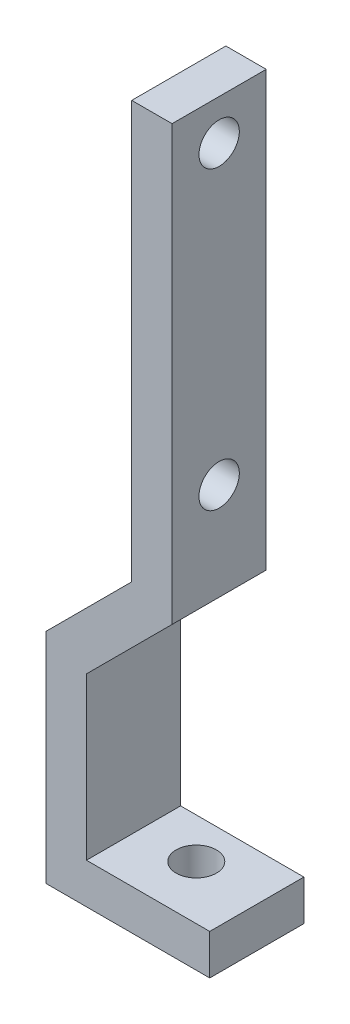
SolidWorks part; units mm, degrees
ref_plane "前视基准面" through (0, 0, 0) normal (0, 0, 1) x (1, 0, 0)
ref_plane "上视基准面" through (0, 0, 0) normal (0, 1, 0) x (1, 0, 0)
ref_plane "右视基准面" through (0, 0, 0) normal (1, 0, 0) x (0, 0, -1)
sketch "草图1" plane through (0, 0, 0) normal (0, 0, 1) x (1, 0, 0)
  line L0 (-3.6411, 21.9867) -> (-3.6411, -9.0133)
  line L1 (-3.6411, -9.0133) -> (-10.005, -15.3772)
  line L2 (-10.005, -15.3772) -> (-10.005, -31.6199)
  line L3 (-10.005, -31.6199) -> (2.1589, -31.6199)
  line L4 (2.1589, -31.6199) -> (2.1589, -28.6199)
  line L5 (2.1589, -28.6199) -> (-7.005, -28.6199)
  line L6 (-7.005, -28.6199) -> (-7.005, -16.6199)
  line L7 (-7.005, -16.6199) -> (-0.6411, -10.2559)
  line L8 (-0.6411, -10.2559) -> (-0.6411, 21.9867)
  line L9 (-0.6411, 21.9867) -> (-3.6411, 21.9867)
  line L10 (-2.8411, -28.6199) -> (-2.8411, -31.6199)
  line L11 (-4.3411, -28.6199) -> (-4.3411, -31.6199)
  line L12 (-1.3411, -28.6199) -> (-1.3411, -31.6199)
  dimension "D1" = 3
  dimension "D2" = 3
  dimension "D3" = 3
  dimension "D4" = 3
  dimension "D5" = 31
  dimension "D6" = 12
  dimension "D7" = 9
  dimension "D8" = 1.5
  dimension "D9" = 1.5
  dimension "D10" = 0.8
  dimension "D11" = 5
extrude "凸台-拉伸1" add sketch "草图1" along normal blind 7 contours L11 L5 L6 L7 L8 L9 L0 L1 L2 L3 | L12 L5 L10 L3 | L5 L11 L3 L10 | L5 L12 L3 L4
sketch "草图2" plane through (-3.6411, 0, 0) normal (-1, 0, 0) x (0, 0, 1)
  line L0 (7, 21.9867) -> (0, 21.9867) construction
  line L1 (0, 21.9867) -> (0, -9.0133) construction
  circle A0 centre (3.5, 18.9867) radius 1.5
  circle A1 centre (3.5, -3.0133) radius 1.5
  dimension "D2" = 3
  dimension "D3" = 3
  dimension "D1" = 3
  dimension "D4" = 22
  dimension "D5" = 3.5
  dimension "D6" = 3.5
extrude "切除-拉伸2" cut sketch "草图2" against normal blind 7
sketch "草图4" plane through (0, -28.6199, 0) normal (0, 1, 0) x (1, 0, 0)
  line L0 (2.1589, 0) -> (-7.005, 0) construction
  line L1 (2.1589, -7) -> (2.1589, 0) construction
  circle A0 centre (-2.8411, -3) radius 1.5
  dimension "D2" = 3
  dimension "D1" = 3
  dimension "D3" = 5
extrude "切除-拉伸3" cut sketch "草图4" against normal blind 7
